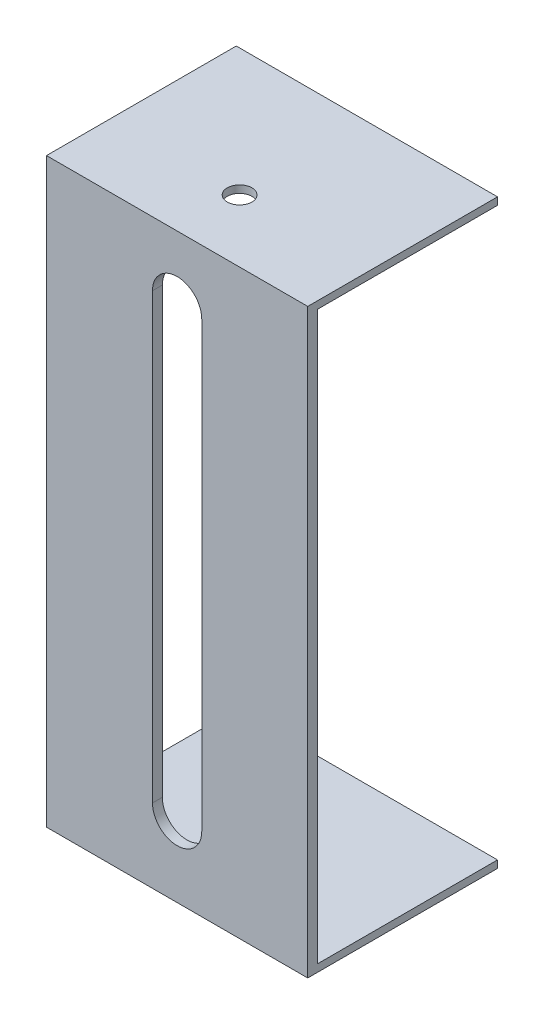
SolidWorks part; units mm, degrees
material "ABS"
ref_plane "Front Plane" through (0, 0, 0) normal (0, 0, 1) x (1, 0, 0)
ref_plane "Top Plane" through (0, 0, 0) normal (0, 1, 0) x (1, 0, 0)
ref_plane "Right Plane" through (0, 0, 0) normal (1, 0, 0) x (0, 0, -1)
sketch "Sketch1" plane through (0, 0, 0) normal (0, 1, 0) x (1, 0, 0)
  line L0 (-42, 31.5) -> (-42, -31.5)
  line L1 (-45, 34.5) -> (45, 34.5)
  line L2 (-45, 34.5) -> (-45, -34.5)
  line L3 (-45, -34.5) -> (45, -34.5)
  line L4 (45, 34.5) -> (45, -34.5)
  line L5 (-45, 34.5) -> (45, -34.5) construction
  line L6 (-45, -34.5) -> (45, 34.5) construction
  line L7 (-42, -31.5) -> (42, -31.5)
  line L8 (42, 31.5) -> (42, -31.5)
  line L9 (-42, 31.5) -> (42, 31.5)
  point P0 (0, 0)
  dimension "D1" = 90
  dimension "D2" = 69
  dimension "D3" = 3
extrude "Boss-Extrude1" add sketch "Sketch1" along normal blind 3
sketch "Sketch2" plane through (0, 3, 0) normal (0, 1, 0) x (1, 0, 0)
  line L1 (-53, 38.5) -> (53, 38.5)
  line L2 (-53, 38.5) -> (-53, -38.5)
  line L3 (-53, -38.5) -> (53, -38.5)
  line L4 (53, 38.5) -> (53, -38.5)
  line L5 (-53, 38.5) -> (53, -38.5) construction
  line L6 (-53, -38.5) -> (53, 38.5) construction
  circle A0 centre (0, -13.15) radius 5
  point P0 (0, 0)
  point P9 (0, 0)
  point P11 (0, 0)
  dimension "D3" = 5
  dimension "D4" = 13.15
  dimension "D1" = 106
  dimension "D2" = 77
extrude "Boss-Extrude3" add sketch "Sketch2" along normal blind 3
sketch "Sketch3" plane through (-53, 0, 0) normal (-1, 0, 0) x (0, -1, 0)
  line L1 (-3, 38.5) -> (227, 38.5)
  line L2 (-3, 38.5) -> (-3, 34.5)
  line L3 (-3, 34.5) -> (227, 34.5)
  line L4 (227, 38.5) -> (227, 34.5)
  dimension "D1" = 230
  dimension "D2" = 4
extrude "Boss-Extrude4" add sketch "Sketch3" against normal up to surface (106 mm away) up to face at (53, 4.5, 0)
sketch "Sketch4" plane through (0, 0, 34.5) normal (0, 0, -1) x (1, 0, 0)
  line L8 (42, 3) -> (42, 216)
  line L9 (42, 216) -> (-42, 216)
  line L10 (-42, 216) -> (-42, 3)
  line L12 (-42, 3) -> (42, 3)
  line L13 (-45, 0) -> (45, 0)
  line L16 (45, 8) -> (45, 219)
  line L17 (45, 219) -> (-45, 219)
  line L18 (-45, 219) -> (-45, 8)
  line L19 (-45, 8) -> (45, 8)
  line L20 (45, 0) -> (45, 219)
  line L21 (45, 219) -> (-45, 219)
  line L22 (-45, 219) -> (-45, 0)
  line L28 (-42, 3) -> (42, 3) construction
  line L29 (-45, 0) -> (45, 0) construction
  dimension "D1" = 8
  dimension "D2" = 3
extrude "Boss-Extrude5" add sketch "Sketch4" along normal blind 2 contours L22 L13 L20 L21 L12 L10 L9 L8
sketch "Sketch5" plane through (-53, 0, 0) normal (-1, 0, 0) x (0, -1, 0)
  line L1 (227, -38.5) -> (230, -38.5)
  line L2 (227, -38.5) -> (227, 38.5)
  line L3 (227, 38.5) -> (230, 38.5)
  line L4 (230, -38.5) -> (230, 38.5)
  line L5 (-6, 38.5) -> (227, 38.5) construction
  line L6 (-6, -38.5) -> (-3, -38.5) construction
  line L7 (-3, -38.5) -> (-3, 34.5) construction
  point P8 (0, 0)
  dimension "D1" = 230
extrude "Boss-Extrude6" add sketch "Sketch5" against normal up to surface (106 mm away) up to face at (53, -72.6667, 11.5)
sketch "Sketch6" plane through (0, -230, 0) normal (0, -1, 0) x (1, 0, 0)
  circle A0 centre (0, 13.15) radius 5 construction
  circle A1 centre (0, 13.15) radius 5
extrude "Cut-Extrude1" cut sketch "Sketch6" against normal up to surface (3 mm away) up to face at (0, -227, -2)
sketch "Sketch7" plane through (0, 0, 38.5) normal (0, 0, 1) x (1, 0, 0)
  line L0 (0, -20) -> (0, -200) construction
  line L1 (10, -20) -> (10, -200)
  line L2 (-10, -20) -> (-10, -200)
  line L3 (53, -230) -> (-53, -230) construction
  arc A0 (10, -20) -> (-10, -20) centre (0, -20) ccw
  arc A1 (-10, -200) -> (10, -200) centre (0, -200) ccw
  point P2 (0, -110)
  point P7 (0, 0)
  dimension "D2" = 180
  dimension "D1" = 20
  dimension "D3" = 30
extrude "Cut-Extrude2" cut sketch "Sketch7" against normal through all
